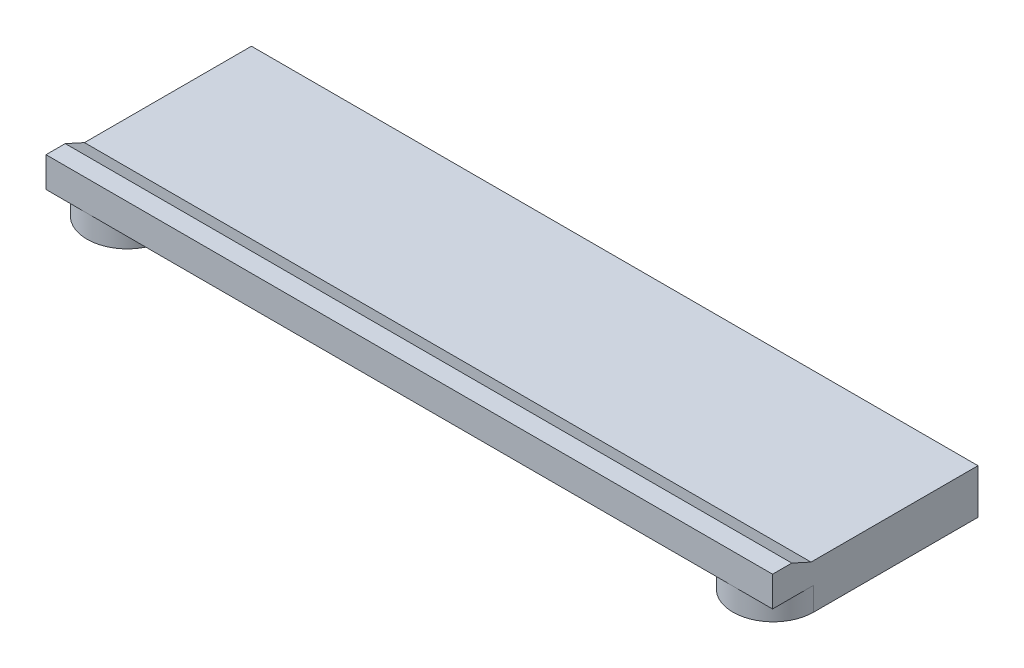
SolidWorks part; units mm, degrees
ref_plane "Alzado" through (0, 0, 0) normal (0, 0, 1) x (1, 0, 0)
ref_plane "Planta" through (0, 0, 0) normal (0, 1, 0) x (1, 0, 0)
ref_plane "Vista lateral" through (0, 0, 0) normal (1, 0, 0) x (0, 0, -1)
sketch "Croquis1" plane through (0, 0, 0) normal (0, 1, 0) x (1, 0, 0)
  line L0 (-55.4958, 0) -> (691.7142, 0)
  line L1 (-55.4958, 0) -> (-55.4958, -211.28)
  line L2 (-55.4958, -211.28) -> (691.7142, -211.28)
  line L3 (691.7142, -211.28) -> (691.7142, 0)
extrude "Saliente-Extruir1" add sketch "Croquis1" along normal blind 22
ref_plane "Plano1" through (0, 22, 0) normal (0, 1, 0) x (1, 0, 0)
sketch "Croquis2" plane through (0, 22, 0) normal (0, 1, 0) x (1, 0, 0)
  line L0 (-55.4958, -171.719) -> (-55.4958, -211.28)
  line L1 (-55.4958, 0) -> (-55.4958, -211.28) construction
  line L2 (-55.4958, -211.28) -> (691.7142, -211.28)
  line L3 (691.7142, -211.28) -> (691.7142, -171.719)
  line L4 (691.7142, -211.28) -> (691.7142, 0) construction
  line L5 (691.7142, -171.719) -> (-55.4958, -171.719)
ref_plane "Plano2" through (0, 31, 0) normal (0, 1, 0) x (1, 0, 0)
sketch "Croquis3" plane through (0, 31, 0) normal (0, 1, 0) x (1, 0, 0)
  line L0 (-55.4958, -211.28) -> (-55.4958, -191.4995)
  line L1 (-55.4958, -171.719) -> (-55.4958, -211.28) construction
  line L2 (-55.4958, -191.4995) -> (691.7142, -191.4995)
  line L3 (691.7142, -211.28) -> (691.7142, -171.719) construction
  line L4 (691.7142, -191.4995) -> (691.7142, -211.28)
  line L5 (691.7142, -211.28) -> (-55.4958, -211.28)
loft "Recubrir1" add profiles "Croquis2", "Croquis3"
ref_plane "Plano3" through (0, -24, 0) normal (0, -1, 0) x (-1, 0, 0)
sketch "Croquis4" plane through (0, -24, 0) normal (0, -1, 0) x (-1, 0, 0)
  line L0 (-691.7142, 0) -> (-608.7912, 0)
  line L1 (-691.7142, 0) -> (55.4958, 0) construction
  line L2 (-608.7912, 0) -> (-608.7912, -169.0612)
  line L3 (-691.7142, -211.28) -> (-691.7142, 0) construction
  line L4 (-691.7142, -169.0612) -> (-691.7142, 0)
  line L5 (55.4958, 0) -> (55.4958, -169.0612)
  line L6 (55.4958, 0) -> (55.4958, -211.28) construction
  line L7 (55.4958, 0) -> (-27.4272, 0)
  line L8 (-27.4272, -169.0612) -> (-26.0753, -168.0349)
  line L9 (-27.4272, 0) -> (-26.0753, -168.0349)
  arc A0 (-608.7912, -169.0612) -> (-691.7142, -169.0612) centre (-650.2527, -169.0612) cw
  arc A1 (55.4958, -169.0612) -> (-27.4272, -169.0612) centre (14.0343, -169.0612) cw
extrude "Saliente-Extruir6" add sketch "Croquis4" against normal blind 39
